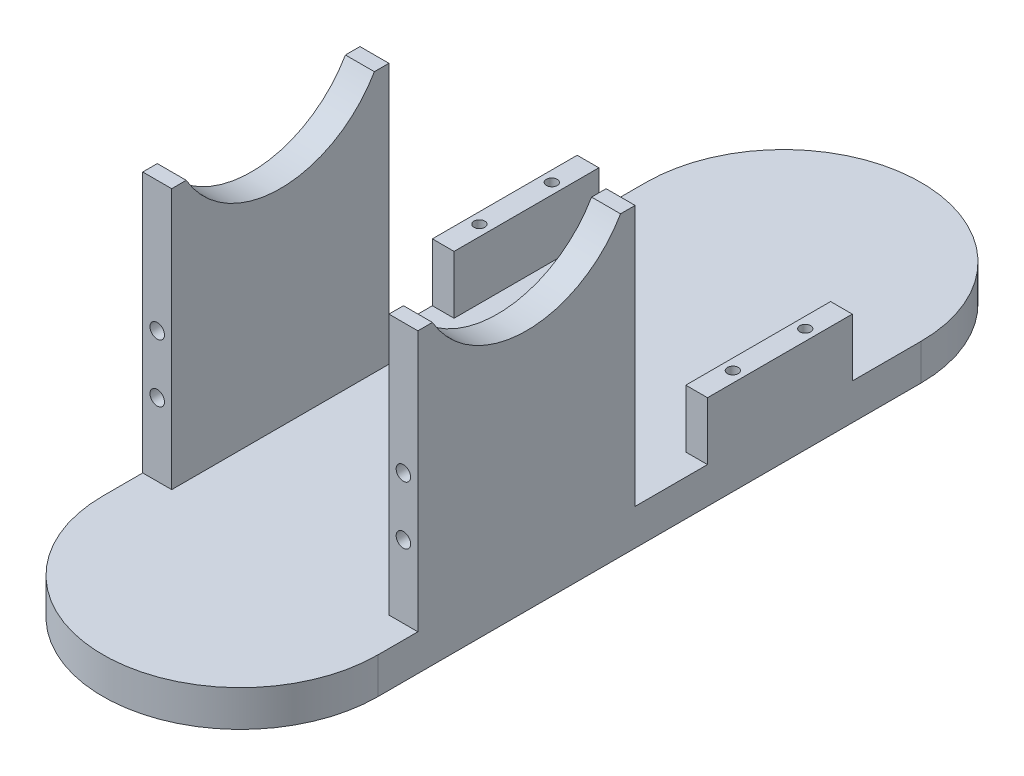
SolidWorks part; units mm, degrees
ref_plane "Front" through (0, 0, 0) normal (0, 0, 1) x (1, 0, 0)
ref_plane "Top" through (0, 0, 0) normal (0, 1, 0) x (1, 0, 0)
ref_plane "Right" through (0, 0, 0) normal (1, 0, 0) x (0, 0, -1)
sketch "草图1" plane through (0, 0, 0) normal (0, 1, 0) x (1, 0, 0)
  line L0 (0, 24.0367) -> (0, 0) construction
  line L1 (0, 0) -> (-31.1152, 0) construction
  line L2 (0, -75) -> (0, 75) construction
  line L3 (-38, -75) -> (-38, 75)
  line L4 (38, -75) -> (38, 75)
  arc A0 (-38, -75) -> (38, -75) centre (0, -75) ccw
  arc A1 (38, 75) -> (-38, 75) centre (0, 75) ccw
  point P6 (0, 0)
extrude "凸台-拉伸1" add sketch "草图1" along normal blind 10
sketch "草图3" plane through (0, 10, 0) normal (0, 1, 0) x (1, 0, 0)
  line L0 (-87.6038, -64) -> (61.1928, -64) construction
  line L1 (-38, 75) -> (-38, -75) construction
  line L2 (-38, -64) -> (-30, -64)
  line L3 (-38, -64) -> (-38, -4)
  line L4 (-38, -4) -> (-30, -4)
  line L5 (-30, -64) -> (-30, -4)
  line L6 (38, -75) -> (38, 75) construction
  line L7 (38, -64) -> (30, -64)
  line L8 (38, -64) -> (38, -4)
  line L9 (38, -4) -> (30, -4)
  line L10 (30, -64) -> (30, -4)
  dimension "D1" = 64
  dimension "D2" = 60
  dimension "D3" = 8
  dimension "D4" = 8
  dimension "D5" = 60
extrude "凸台-拉伸2" add sketch "草图3" along normal blind 72
sketch "草图4" plane through (0, 10, 0) normal (0, 1, 0) x (1, 0, 0)
  line L0 (-57.3538, 16) -> (64.3655, 16) construction
  line L1 (-38, 75) -> (-38, -4) construction
  line L2 (-38, 16) -> (-32, 16)
  line L3 (-38, 16) -> (-38, 56)
  line L4 (-38, 56) -> (-32, 56)
  line L5 (-32, 16) -> (-32, 56)
  line L6 (38, -4) -> (38, 75) construction
  line L7 (38, 16) -> (32, 16)
  line L8 (38, 16) -> (38, 56)
  line L9 (38, 56) -> (32, 56)
  line L10 (32, 16) -> (32, 56)
  dimension "D1" = 16
  dimension "D2" = 6
  dimension "D3" = 40
  dimension "D4" = 6
extrude "凸台-拉伸3" add sketch "草图4" along normal blind 16
sketch "草图5" plane through (38, 0, 0) normal (1, 0, 0) x (0, 0, -1)
  line L0 (-64, 82) -> (-4, 82) construction
  circle A0 centre (-34, 97) radius 30
  dimension "D1" = 15
extrude "切除-拉伸1" cut sketch "草图5" against normal through all
sketch "草图6" plane through (0, 0, 64) normal (0, 0, 1) x (1, 0, 0)
  line L0 (-49.7987, 46) -> (50.3023, 46) construction
  line L1 (-49.7987, 30) -> (51.0857, 30) construction
  line L2 (-38, 0) -> (38, 0) construction
  circle A0 centre (-34, 46) radius 2
  circle A1 centre (-34, 30) radius 2
  circle A2 centre (34, 46) radius 2
  circle A3 centre (34, 30) radius 2
  dimension "D1" = 46
  dimension "D2" = 30
extrude "切除-拉伸2" cut sketch "草图6" against normal blind 10
sketch "草图7" plane through (0, 26, 0) normal (0, 1, 0) x (1, 0, 0)
  line L0 (-38, 36) -> (38, 36) construction
  line L1 (-38, 56) -> (-38, 16) construction
  line L2 (38, 16) -> (38, 56) construction
  line L3 (-32, 16) -> (-32, 56) construction
  line L4 (-38, 16) -> (-32, 16) construction
  line L5 (35, 16) -> (35, 56) construction
  line L6 (32, 16) -> (38, 16) construction
  line L7 (38, 56) -> (32, 56) construction
  circle A0 centre (-35, 26) radius 1.5
  circle A1 centre (-35, 46) radius 1.5
  circle A2 centre (35, 26) radius 1.5
  circle A3 centre (35, 46) radius 1.5
  point P6 (-32, 36)
  dimension "D2" = 20
  dimension "D1" = 10
extrude "切除-拉伸3" cut sketch "草图7" against normal blind 10
